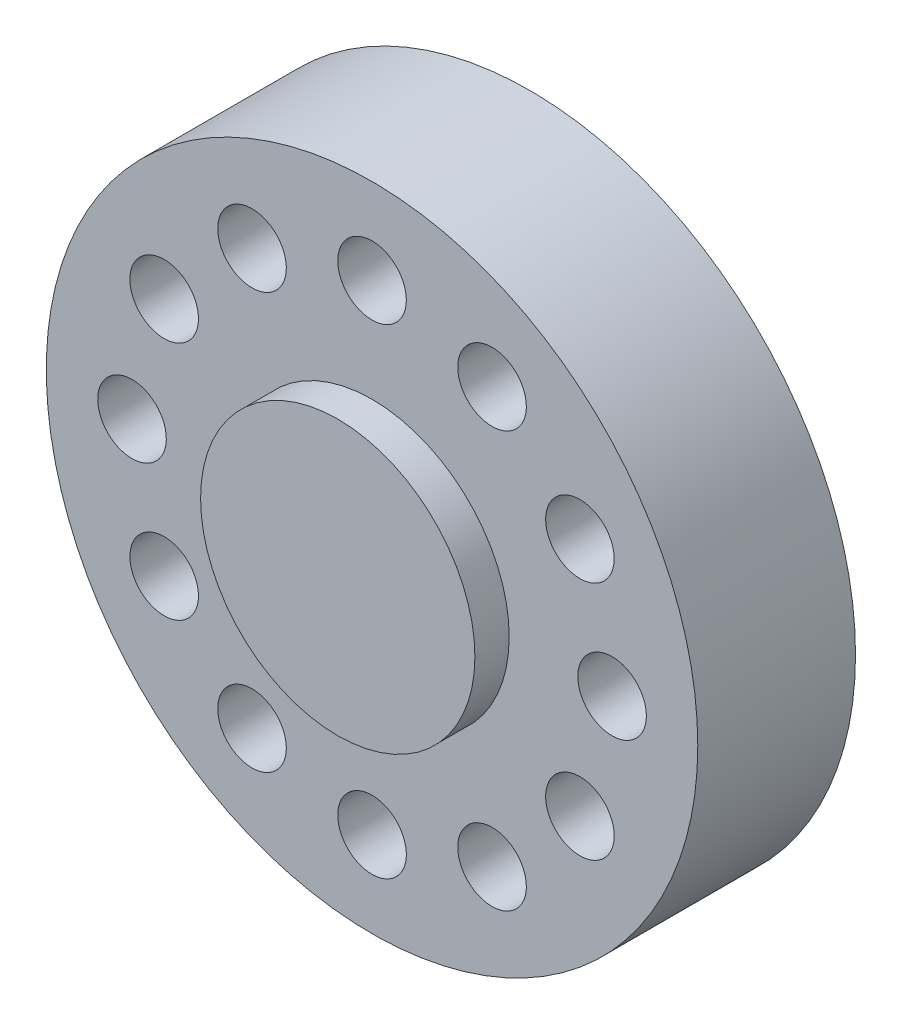
SolidWorks part; units mm, degrees
ref_plane "Plan de face" through (0, 0, 0) normal (0, 0, 1) x (1, 0, 0)
ref_plane "Plan de dessus" through (0, 0, 0) normal (0, 1, 0) x (1, 0, 0)
ref_plane "Plan de droite" through (0, 0, 0) normal (1, 0, 0) x (0, 0, -1)
sketch "Esquisse1" plane through (0, 0, 0) normal (0, 0, 1) x (1, 0, 0)
  circle A0 centre (-16.7582, 25.7618) radius 9.5
  point P2 (0, 0)
extrude "Boss.-Extru.1" add sketch "Esquisse1" along normal blind 4.6
sketch "Esquisse2" plane through (0, 0, 4.6) normal (0, 0, 1) x (1, 0, 0)
  line L0 (-16.7582, 25.7618) -> (-16.7582, 39.7618) construction
  circle A0 centre (-16.7582, 25.7618) radius 4
  circle A1 centre (-16.7582, 25.7618) radius 9.5 construction
  circle A2 centre (-16.7582, 32.7618) radius 1
  dimension "D1" = 0
  dimension "D2" = 7
pattern_circular "Répétition circulaire1" count 12 every 30 about axis through (-16.7582, 25.7618, 4.6) along (0, 0, 1) of "Boss.-Extru.1"
extrude "Boss.-Extru.4" add sketch "Esquisse2" along normal blind 1 contours A0
sketch "Esquisse7" plane through (0, 0, 4.6) normal (0, 0, 1) x (1, 0, 0)
  line L0 (-16.7582, 25.7618) -> (-16.7582, 39.7618) construction
  circle A0 centre (-16.7582, 32.7618) radius 1
  dimension "D1" = 7
extrude "Enlèv. mat.-Extru.1" cut sketch "Esquisse7" against normal blind 4.6
pattern_circular "Répétition circulaire2" count 12 every 30 about axis through (-16.7582, 25.7618, 0) along (0, 0, 1) of "Enlèv. mat.-Extru.1"
